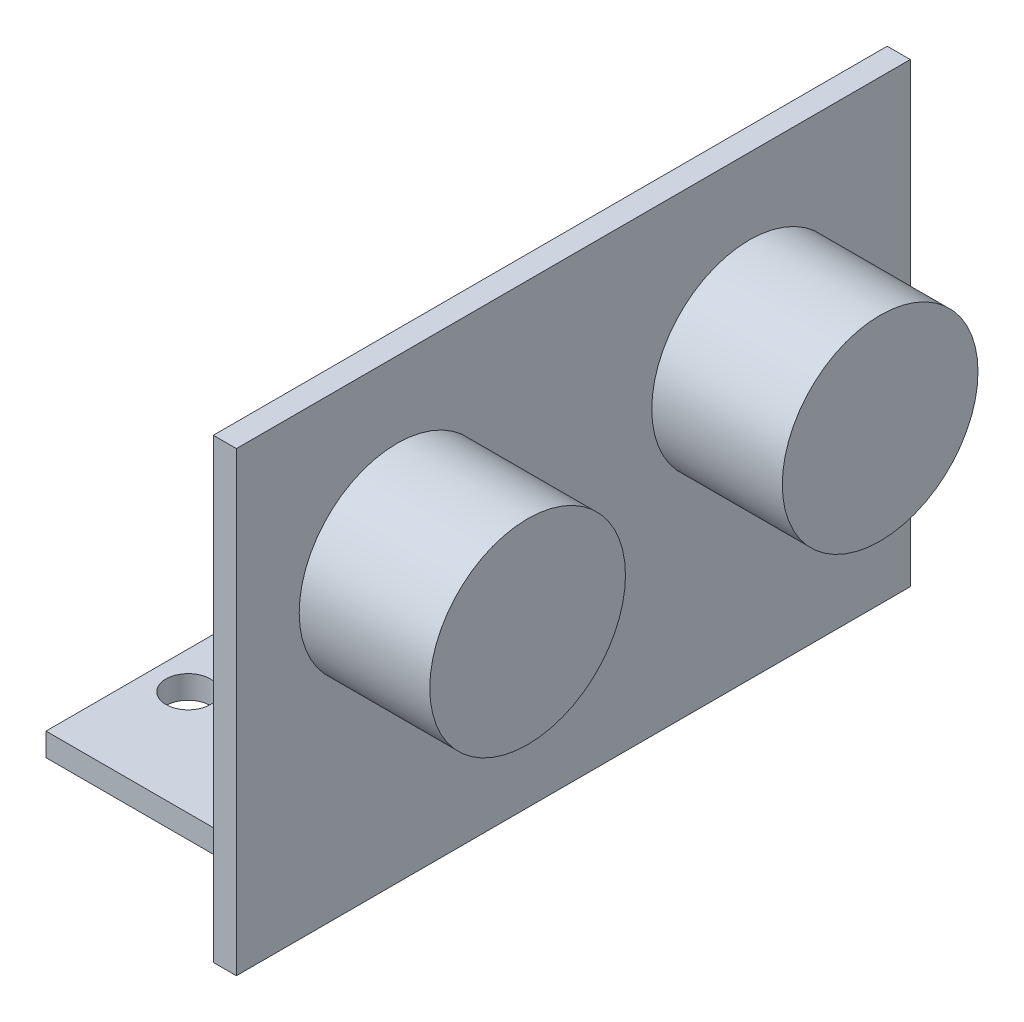
SolidWorks part; units mm, degrees
ref_plane "Plan de face" through (0, 0, 0) normal (0, 0, 1) x (1, 0, 0)
ref_plane "Plan de dessus" through (0, 0, 0) normal (0, 1, 0) x (1, 0, 0)
ref_plane "Plan de droite" through (0, 0, 0) normal (1, 0, 0) x (0, 0, -1)
sketch "Esquisse1" plane through (0, 0, 0) normal (1, 0, 0) x (0, 0, -1)
  line L0 (0, 0) -> (0, 37)
  line L1 (0, 0) -> (54.61, 0)
  line L2 (54.61, 0) -> (54.61, 37)
  line L3 (54.61, 37) -> (0, 37)
extrude "Boss.-Extru.1" add sketch "Esquisse1" along normal blind 1.87 contours L3 L0 L1 L2
sketch "Esquisse2" plane through (1.87, 0, 0) normal (1, 0, 0) x (0, 0, -1)
  circle A0 centre (13.02, 22.93) radius 7.93
  circle A1 centre (41.59, 22.93) radius 7.93
extrude "Boss.-Extru.2" add sketch "Esquisse2" along normal blind 10.58
sketch "Esquisse3" plane through (0, 0, 0) normal (-1, 0, 0) x (0, 0, 1)
  line L8 (0, 0) -> (-54.61, 0) construction
  line L13 (-47.02, 1.87) -> (-7.59, 1.87)
  line L14 (-47.02, 1.87) -> (-47.02, 0)
  line L15 (-47.02, 0) -> (-7.59, 0)
  line L16 (-7.59, 1.87) -> (-7.59, 0)
extrude "Boss.-Extru.3" add sketch "Esquisse3" along normal blind 21.15
hole_wizard "Dégagement M31" positions "Esquisse3D2" profile "Esquisse5" hole size "M3" standard "Ansi Metric"
sketch3d "Esquisse3D2"
  line L0 (-21.15, 1.87, -47.02) -> (0, 1.87, -47.02) construction
  line L1 (-21.15, 1.87, -7.59) -> (-21.15, 1.87, -47.02) construction
  line L2 (-21.15, 1.87, -7.59) -> (0, 1.87, -7.59) construction
  point P0 (-18.15, 1.87, -38.5)
  point P2 (-18.15, 1.87, -16.11)
  dimension "D1" = 8.52
  dimension "D2" = 3
  dimension "D3" = 8.52
  dimension "D4" = 3
sketch "Esquisse5" plane through (-18.15, 1.87, -38.5) normal (1, 0, 0) x (0, 0, 1)
  line L0 (0, 0) -> (0, 3.0715)
  line L1 (0, 3.0715) -> (1.8, 1.99)
  line L2 (1.8, 1.99) -> (1.8, 0)
  line L5 (1.8, 0) -> (0, 0)
  line L10 (0, 3.0715) -> (-1.8, 1.99) construction
  line L11 (0, -6.35) -> (0, 107.95) construction
  dimension "Diamètre du perçage" = 3.6
  dimension "Profondeur du perçage" = 1.99
  dimension "Angle de pointe" = 118
